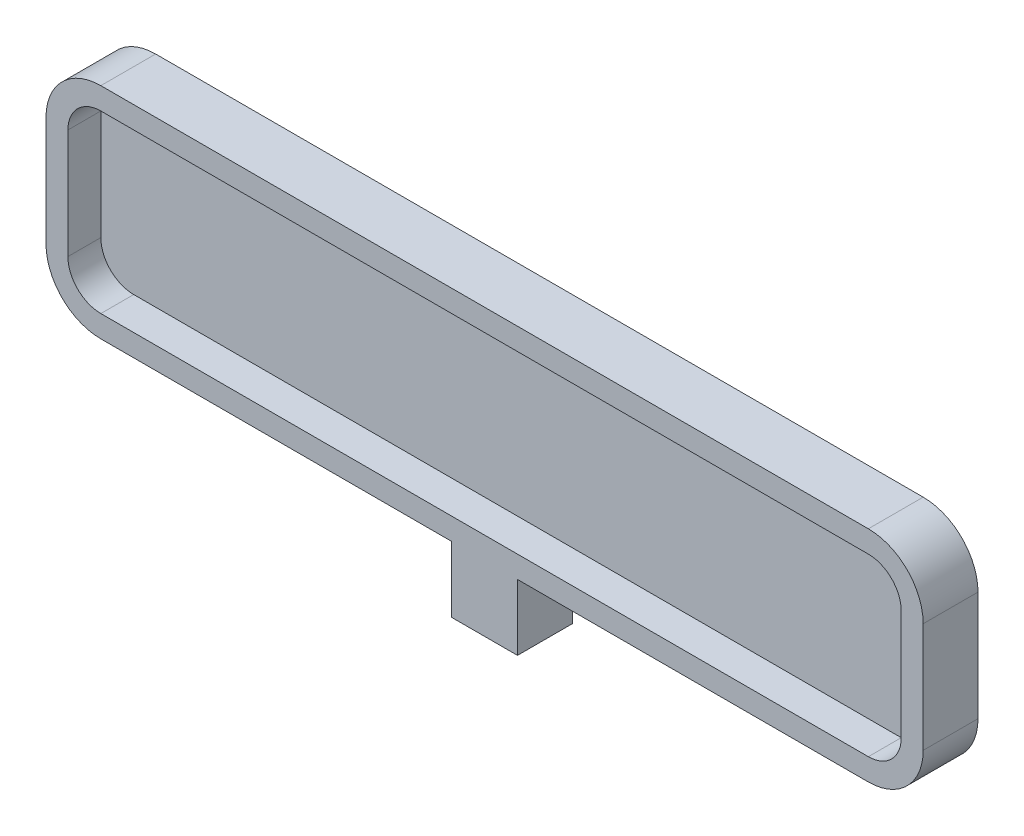
SolidWorks part; units mm, degrees
ref_plane "Front Plane" through (0, 0, 0) normal (0, 0, 1) x (1, 0, 0)
ref_plane "Top Plane" through (0, 0, 0) normal (0, 1, 0) x (1, 0, 0)
ref_plane "Right Plane" through (0, 0, 0) normal (1, 0, 0) x (0, 0, -1)
sketch "Sketch2" plane through (0, 0, 0) normal (0, 0, 1) x (1, 0, 0)
  line L1 (-40, -10) -> (40, -10)
  line L2 (-40, -10) -> (-40, 10)
  line L3 (-40, 10) -> (40, 10)
  line L4 (40, -10) -> (40, 10)
  line L5 (-40, -10) -> (40, 10) construction
  line L6 (-40, 10) -> (40, -10) construction
  point P0 (0, 0)
  dimension "D1" = 80
  dimension "D2" = 20
extrude "Boss-Extrude1" add sketch "Sketch2" along normal mid plane 5
fillet "Fillet1" radius 5 2 edges at (40, -10, 0) (-40, -10, 0)
fillet "Fillet2" radius 5 2 edges at (-40, 10, 0) (40, 10, 0)
shell "Shell1" thickness 2
sketch "Sketch3" plane through (0, -10, 0) normal (0, -1, 0) x (1, 0, 0)
  line L0 (-35, 2.5) -> (35, 2.5) construction
  line L1 (-3, -2.5) -> (3, -2.5)
  line L2 (-3, -2.5) -> (-3, 2.5)
  line L3 (-3, 2.5) -> (3, 2.5)
  line L4 (3, -2.5) -> (3, 2.5)
  line L5 (-3, -2.5) -> (3, 2.5) construction
  line L6 (-3, 2.5) -> (3, -2.5) construction
  point P0 (0, 0)
  dimension "D1" = 6
extrude "Boss-Extrude2" add sketch "Sketch3" along normal blind 6
sketch "Sketch4" plane through (0, -16, 0) normal (0, -1, 0) x (1, 0, 0)
  circle A0 centre (0, 0) radius 1.425
  dimension "D1" = 2.85
extrude "Cut-Extrude1" cut sketch "Sketch4" against normal blind 4
